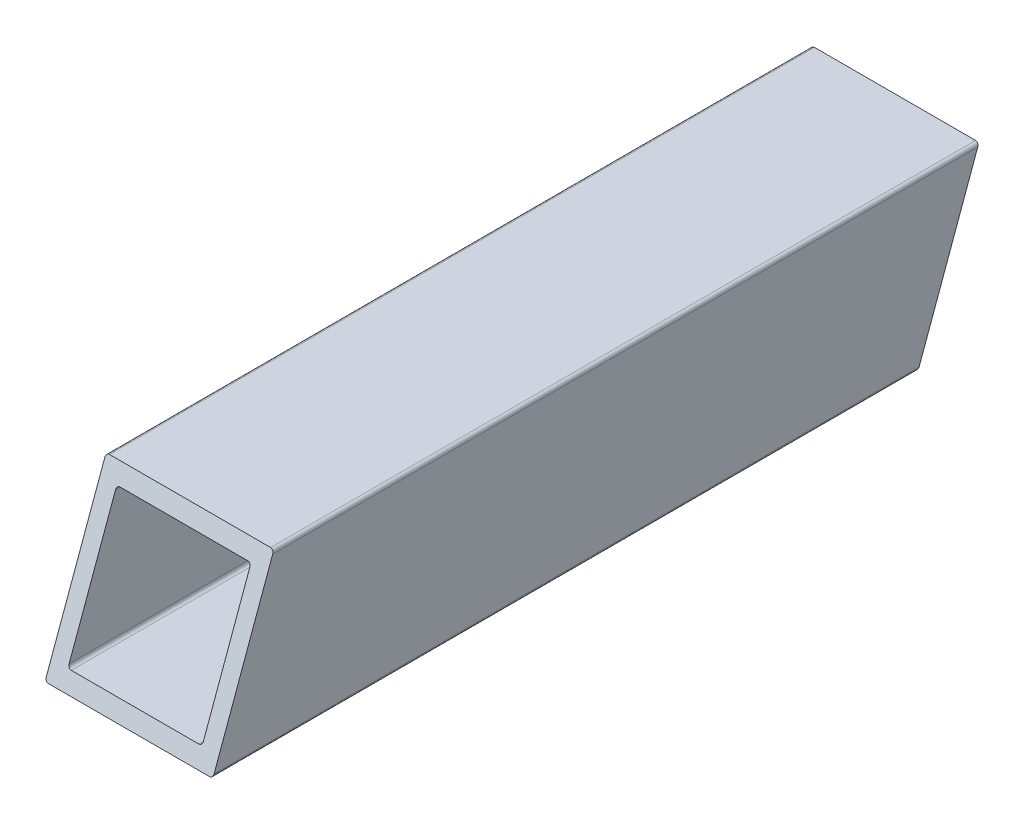
SolidWorks part; units mm, degrees
ref_plane "前基準面" through (0, 0, 0) normal (0, 0, 1) x (1, 0, 0)
ref_plane "上基準面" through (0, 0, 0) normal (0, 1, 0) x (1, 0, 0)
ref_plane "右基準面" through (0, 0, 0) normal (1, 0, 0) x (0, 0, -1)
sketch "草圖1" plane through (0, 0, 0) normal (0, 0, 1) x (1, 0, 0)
  line L1 (-5, 5) -> (5, 5)
  line L2 (-5, 5) -> (-5, -5)
  line L3 (-5, -5) -> (5, -5)
  line L4 (5, 5) -> (5, -5)
  line L5 (-4, 4) -> (4, 4)
  line L6 (-4, 4) -> (-4, -4)
  line L7 (-4, -4) -> (4, -4)
  line L8 (4, 4) -> (4, -4)
  dimension "D1" = 10
  dimension "D2" = 5
  dimension "D3" = 10
  dimension "D4" = 5
  dimension "D5" = 1
  dimension "D6" = 1
  dimension "D7" = 1
  dimension "D8" = 1
extrude "填料-伸長1" add sketch "草圖1" along normal blind 200
fillet "圓角1" radius 0.2 8 edges at (4, 4, 100) (-4, 4, 100) (-5, -5, 100) (4, -4, 100) (5, -5, 100) (-5, 5, 100) (-4, -4, 100) (5, 5, 100)
sketch "草圖2" plane through (5, 0, 0) normal (1, 0, 0) x (0, 0, -1)
  line L0 (0, 5) -> (0, -5)
  line L1 (0, -5) -> (-3.6397, -5)
  line L2 (0, -5) -> (-200, -5) construction
  line L3 (-3.6397, -5) -> (0, 5)
  dimension "D1" = 110
extrude "除料-伸長1" cut sketch "草圖2" against normal through all
sketch "草圖3" plane through (5, 0, 0) normal (1, 0, 0) x (0, 0, -1)
  line L0 (-45.6397, -5) -> (-42, 5)
  line L1 (-3.6397, -5) -> (-200, -5) construction
  line L2 (-200, 5) -> (0, 5) construction
  line L3 (-42, 5) -> (-200, 5)
  line L4 (-200, 5) -> (-200, -5)
  line L5 (-200, -5) -> (-45.6397, -5)
  dimension "D1" = 42
  dimension "D2" = 110
extrude "除料-伸長2" cut sketch "草圖3" against normal through all
